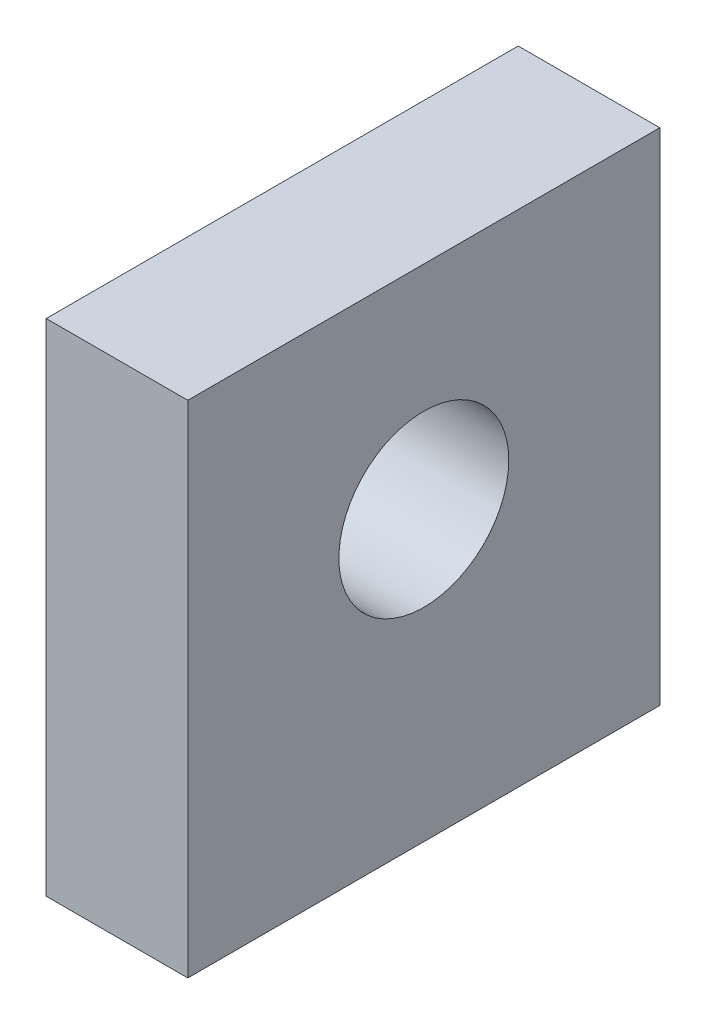
SolidWorks part; units mm, degrees
ref_plane "Alzado" through (0, 0, 0) normal (0, 0, 1) x (1, 0, 0)
ref_plane "Planta" through (0, 0, 0) normal (0, 1, 0) x (1, 0, 0)
ref_plane "Vista lateral" through (0, 0, 0) normal (1, 0, 0) x (0, 0, -1)
sketch "Croquis1" plane through (0, 0, 0) normal (1, 0, 0) x (0, 0, -1)
  line L1 (-25, -26.5) -> (25, -26.5)
  line L2 (-25, -26.5) -> (-25, 26.5)
  line L3 (-25, 26.5) -> (25, 26.5)
  line L4 (25, -26.5) -> (25, 26.5)
  line L5 (-25, -26.5) -> (25, 26.5) construction
  line L6 (-25, 26.5) -> (25, -26.5) construction
  circle A0 centre (0, 4) radius 9
  point P0 (0, 0)
  dimension "D4" = 18
  dimension "D1" = 53
  dimension "D2" = 50
  dimension "D3" = 30.5
extrude "Saliente-Extruir1" add sketch "Croquis1" along normal blind 15
